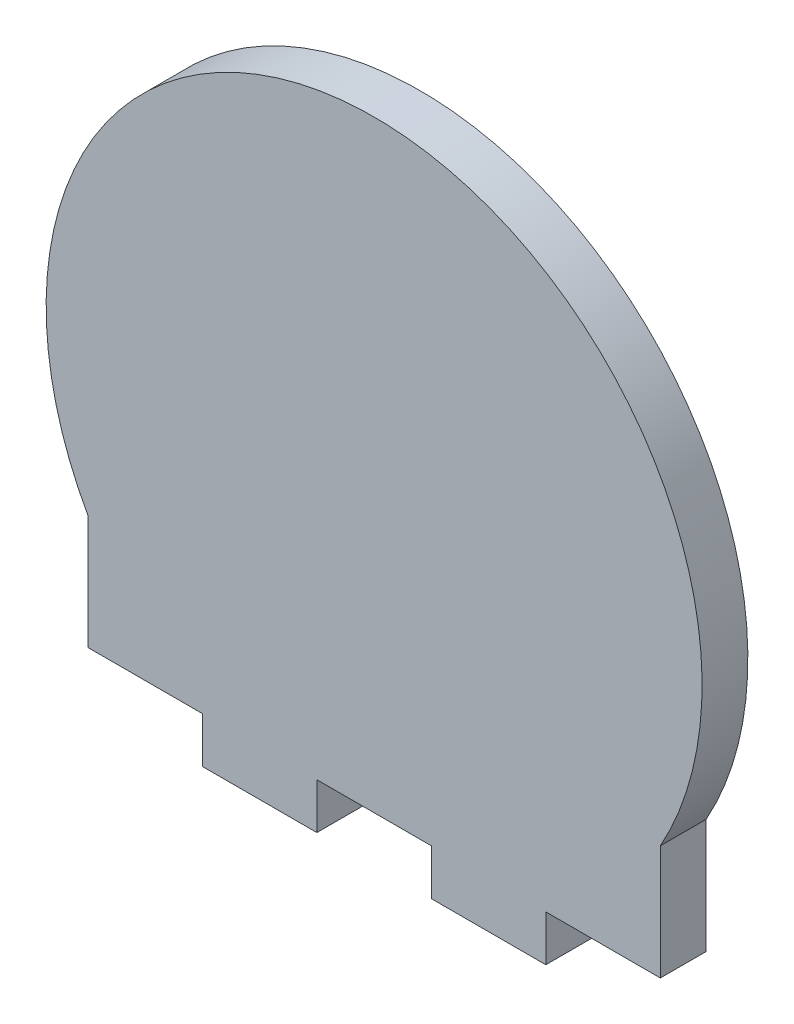
SolidWorks part; units mm, degrees
ref_plane "Front Plane" through (0, 0, 0) normal (0, 0, 1) x (1, 0, 0)
ref_plane "Top Plane" through (0, 0, 0) normal (0, 1, 0) x (1, 0, 0)
ref_plane "Right Plane" through (0, 0, 0) normal (1, 0, 0) x (0, 0, -1)
sketch "Sketch1" plane through (0, 0, 0) normal (0, 0, 1) x (1, 0, 0)
  line L0 (0, 0) -> (10, 0)
  line L1 (10, 0) -> (10, -4)
  line L2 (10, -4) -> (20, -4)
  line L3 (20, -4) -> (20, 0)
  line L4 (20, 0) -> (30, 0)
  line L5 (30, 0) -> (30, -4)
  line L6 (30, -4) -> (40, -4)
  line L7 (40, -4) -> (40, 0)
  line L8 (40, 0) -> (50, 0)
  line L9 (50, 0) -> (50, 10)
  line L11 (0, 10) -> (0, 0)
  arc A0 (0, 10) -> (50, 10) centre (25, 23.9861) cw
  dimension "D1" = 10
  dimension "D2" = 50
  dimension "D3" = 4
  dimension "D4" = 10
extrude "Boss-Extrude1" add sketch "Sketch1" along normal blind 4
